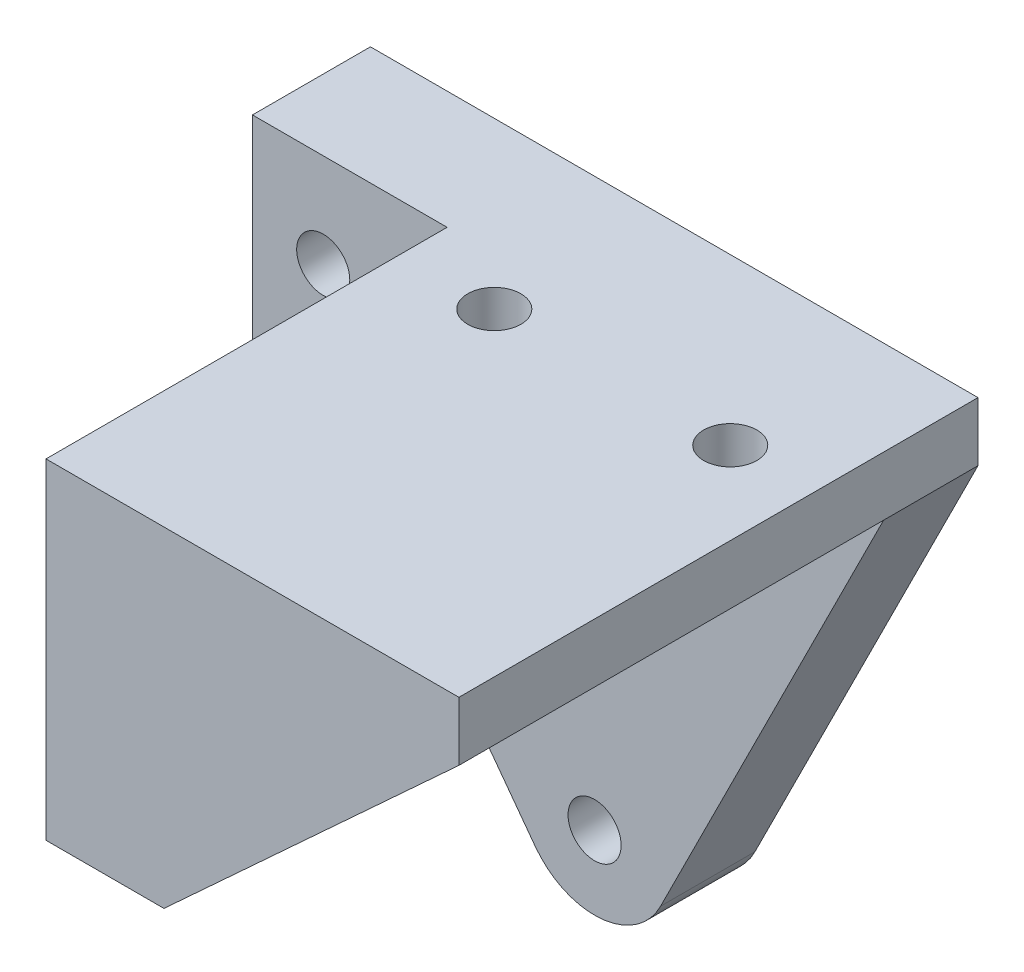
SolidWorks part; units mm, degrees
material "Printed PLA"
ref_plane "Front Plane" through (0, 0, 0) normal (0, 0, 1) x (1, 0, 0)
ref_plane "Top Plane" through (0, 0, 0) normal (0, 1, 0) x (1, 0, 0)
ref_plane "Right Plane" through (0, 0, 0) normal (1, 0, 0) x (0, 0, -1)
sketch "Sketch1" plane through (0, 0, 0) normal (0, 1, 0) x (1, 0, 0)
  line L1 (0, 0) -> (-26.5, 0)
  line L2 (0, 0) -> (0, 40)
  line L3 (0, 40) -> (-10, 40)
  line L4 (-26.5, 0) -> (-26.5, 10)
  line L7 (-26.5, 10) -> (-10, 10)
  line L8 (-10, 40) -> (-10, 10)
  dimension "D1" = 10
  dimension "D2" = 16.5
  dimension "D3" = 30
extrude "Boss-Extrude1" add sketch "Sketch1" along normal blind 28
sketch "Sketch2" plane through (-26.5, 0, 0) normal (-1, 0, 0) x (0, 0, 1)
  line L0 (0, 28) -> (0, 0)
  line L1 (0, 0) -> (8, 0)
  line L2 (8, 0) -> (8, 8)
  line L3 (8, 16) -> (8, 28)
  line L4 (8, 28) -> (0, 28)
  line L5 (-10, 28) -> (-10, 0) construction
  arc A0 (8, 8) -> (8, 16) centre (8, 12) cw
  dimension "D1" = 4
  dimension "D2" = 16
  dimension "D3" = 18
extrude "Boss-Extrude2" add sketch "Sketch2" against normal blind 12
sketch "Sketch3" plane through (0, 0, 8) normal (0, 0, 1) x (1, 0, 0)
  line L0 (-20.5, 4) -> (-20.5, 20) construction
  line L1 (-20.5, 4) -> (-20.5, 0) construction
  line L2 (-14.5, 0) -> (-26.5, 0) construction
  line L3 (-26.5, 12) -> (-20.5, 12) construction
  line L4 (-26.5, 16) -> (-26.5, 8) construction
  circle A0 centre (-20.5, 20) radius 2.25
  circle A1 centre (-20.5, 4) radius 2.25
  dimension "D1" = 4.5
  dimension "D2" = 16
extrude "Cut-Extrude1" cut sketch "Sketch3" against normal through all
sketch "Sketch4" plane through (0, 0, 0) normal (1, 0, 0) x (0, 0, -1)
  line L0 (34, 17.5) -> (22, 17.5) construction
  line L1 (0, 28) -> (40, 28) construction
  line L2 (40, 28) -> (40, 0) construction
  circle A0 centre (22, 17.5) radius 2.25 construction
  circle A1 centre (34, 17.5) radius 2.25
  dimension "D3" = 4.5
  dimension "D4" = 6
  dimension "D1" = 10.5
  dimension "D2" = 12
extrude "Cut-Extrude2" cut sketch "Sketch4" against normal through all
sketch "Sketch5" plane through (0, 0, 0) normal (1, 0, 0) x (0, 0, -1)
  line L0 (40, 28) -> (40, 0) construction
  line L1 (0, 28) -> (40, 28)
  line L2 (0, 28) -> (0, 23)
  line L3 (0, 23) -> (40, 23)
  line L4 (40, 28) -> (40, 23)
  dimension "D1" = 5
extrude "Boss-Extrude3" add sketch "Sketch5" along normal blind 25
sketch "Sketch6" plane through (0, 23, 0) normal (0, -1, 0) x (1, 0, 0)
  line L0 (25, 0) -> (25, -40) construction
  line L1 (25, 0) -> (0, 0) construction
  line L2 (-2, -14) -> (18, -14) construction
  circle A0 centre (-2, -14) radius 2.25
  circle A1 centre (18, -14) radius 2.25
  dimension "D1" = 7
  dimension "D2" = 14
  dimension "D3" = 4.5
  dimension "D4" = 20
extrude "Cut-Extrude3" cut sketch "Sketch6" along normal blind 10 and the other way through all
sketch "Sketch7" plane through (0, 0, 0) normal (1, 0, 0) x (0, 0, -1)
  line L0 (0, 23) -> (40, 23) construction
  line L1 (10.5, 23) -> (17.5, 23)
  line L2 (10.5, 23) -> (10.5, 18)
  line L3 (10.5, 18) -> (17.5, 18)
  line L4 (17.5, 23) -> (17.5, 18)
  line L5 (14, 18) -> (14, 13) construction
  line L6 (16.25, 13) -> (11.75, 13) construction
  dimension "D1" = 7
  dimension "D2" = 5
extrude "Cut-Extrude4" cut sketch "Sketch7" against normal blind 10
sketch "Sketch8" plane through (0, 0, 0) normal (0, 0, 1) x (1, 0, 0)
  line L0 (-14.5, 12) -> (0.5, 12) construction
  line L1 (-14.5, 8) -> (-14.5, 16) construction
  line L2 (0.5, 12) -> (0.5, -12) construction
  line L3 (-9.5, -9) -> (-4.5223, -15.7201)
  line L4 (6.0894, -14.7965) -> (25, 23)
  line L5 (25, 23) -> (0, 23)
  line L6 (0, 23) -> (0, 0)
  line L7 (0, 0) -> (-26.5, 0)
  line L9 (-26.5, 0) -> (-10.9225, -7.8046)
  circle A0 centre (0.5, -12) radius 2.25
  arc A1 (-4.5223, -15.7201) -> (6.0894, -14.7965) centre (0.5, -12) ccw
  arc A2 (-10.9225, -7.8046) -> (-9.5, -9) centre (-12.7143, -11.3809) cw
  dimension "D1" = 24
  dimension "D2" = 4.5
  dimension "D4" = 4
  dimension "D5" = 4
  dimension "D7" = 10
  dimension "D3" = 15
  dimension "D6" = 3
extrude "Boss-Extrude4" add sketch "Sketch8" against normal blind 8
sketch "Sketch9" plane through (0, 0, -40) normal (0, 0, -1) x (-1, 0, 0)
  line L0 (-25, 23) -> (0, 0)
  line L1 (0, 0) -> (0, 23) construction
  line L2 (0, 23) -> (-25, 23) construction
  line L3 (0, 0) -> (10, 0)
  line L4 (10, 0) -> (10, 28)
  line L5 (10, 28) -> (-25, 28)
  line L6 (-25, 28) -> (-25, 23)
extrude "Boss-Extrude6" add sketch "Sketch9" along normal blind 4
sketch "Sketch10" plane through (-14.5, 0, 0) normal (1, 0, 0) x (0, 0, -1)
  line L1 (-8, 28) -> (0, 28)
  line L2 (-8, 28) -> (-8, 0)
  line L3 (-8, 0) -> (0, 0)
  line L4 (0, 28) -> (0, 0)
extrude "Cut-Extrude5" cut sketch "Sketch10" against normal through all
mirror "Mirror1" about plane through (0, 28, 0) normal (0, 0, -1) of bodies 111
delete or keep bodies "Body-Delete1" type delete bodies bodies 111
